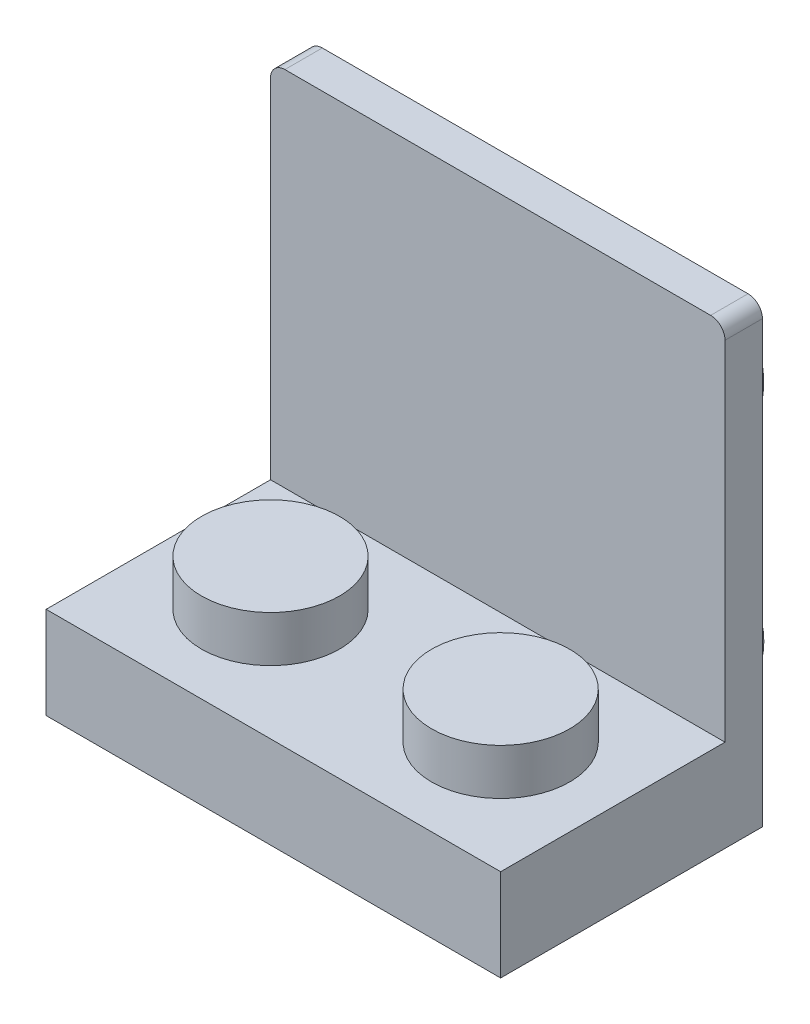
SolidWorks part; units mm, degrees
material "ABS"
ref_plane "Front Plane" through (0, 0, 0) normal (0, 0, 1) x (1, 0, 0)
ref_plane "Top Plane" through (0, 0, 0) normal (0, 1, 0) x (1, 0, 0)
ref_plane "Right Plane" through (0, 0, 0) normal (1, 0, 0) x (0, 0, -1)
sketch "Sketch1" plane through (0, 0, 0) normal (0, 0, 1) x (1, 0, 0)
  line L1 (0, 0) -> (15.8, 0)
  line L2 (0, 0) -> (0, 3.2)
  line L3 (0, 3.2) -> (15.8, 3.2)
  line L4 (15.8, 0) -> (15.8, 3.2)
  line L5 (0, 0) -> (15.8, 3.2) construction
  line L6 (0, 3.2) -> (15.8, 0) construction
  point P4 (7.9, 1.6)
  dimension "D1" = 15.8
  dimension "D2" = 3.2
extrude "Boss-Extrude1" add sketch "Sketch1" against normal blind 7.8
sketch "Sketch2" plane through (0, 3.2, 0) normal (0, 1, 0) x (1, 0, 0)
  line L0 (15.8, 0) -> (0, 0) construction
  circle A0 centre (3.9, 3.9) radius 2.4
  dimension "D1" = 4.8
  dimension "D2" = 3.9
  dimension "D3" = 3.9
extrude "Boss-Extrude2" add sketch "Sketch2" along normal blind 1.6
pattern_linear "LPattern1" count 2 spacing 8 along (0, 0, 1) count 4 spacing 8 along (1, 0, 0) of "Boss-Extrude2"
shell "Shell1" thickness 0.8
sketch "Sketch3" plane through (0, 2.4, 0) normal (0, -1, 0) x (1, 0, 0)
  line L0 (0, 0) -> (15.8, 0) construction
  line L1 (0, -7.8) -> (0, 0) construction
  circle A0 centre (7.9, -3.9) radius 1.5
  circle A1 centre (7.9, -3.9) radius 0.6
  dimension "D1" = 3
  dimension "D2" = 1.2
  dimension "D3" = 3.9
  dimension "D4" = 7.9
extrude "Boss-Extrude3" add sketch "Sketch3" along normal offset from surface (2.2 mm away) 0.2 up to face at (7.9, 0, -3.9)
sketch "Sketch4" plane through (0, 0, -7.8) normal (0, 0, -1) x (-1, 0, 0)
  line L0 (-15.8, 0) -> (-15.8, 7.9)
  line L1 (-15.8, 7.9) -> (0, 7.9)
  line L2 (0, 7.9) -> (0, 0)
  line L3 (0, 0) -> (-15.8, 0)
  dimension "D1" = 7.9
extrude "Boss-Extrude4" add sketch "Sketch4" along normal blind 1.3
sketch "Sketch5" plane through (0, 0, -9.1) normal (0, 0, -1) x (-1, 0, 0)
  line L0 (0, 7.9) -> (-15.8, 7.9) construction
  line L1 (-15.8, 7.9) -> (-15.8, 0) construction
  circle A0 centre (-11.9, 4) radius 2.35
  circle A1 centre (-11.9, 4) radius 1.65
  dimension "D1" = 4.7
  dimension "D4" = 0.7
  dimension "D2" = 3.9
  dimension "D3" = 3.9
extrude "Boss-Extrude5" add sketch "Sketch5" along normal blind 1.6
pattern_linear "LPattern2" count 2 spacing 8 along (-1, 0, 0) of "Boss-Extrude5"
sketch "Sketch7" plane through (0, 0, -7) normal (0, 0, 1) x (1, 0, 0)
  line L0 (12.45, 2.4) -> (12.45, 0)
  line L1 (15, 2.4) -> (0.8, 2.4) construction
  line L2 (0.8, 0) -> (15, 0) construction
  line L3 (12.45, 0) -> (11.35, 0)
  line L4 (11.35, 0) -> (11.35, 2.4)
  line L5 (11.35, 2.4) -> (12.45, 2.4)
  line L6 (15.8, 7.9) -> (15.8, 0) construction
  dimension "D1" = 1.1
  dimension "D2" = 3.35
extrude "Boss-Extrude6" add sketch "Sketch7" along normal blind 0.5
pattern_linear "LPattern3" count 3 spacing 4 along (-1, 0, 0) of "Boss-Extrude6"
ref_plane "Plane1" [suppressed] through (0, 7.9, 0) normal (0, 1, 0) x (1, 0, 0)
sketch "Sketch8" plane through (0, 7.9, 0) normal (0, 1, 0) x (1, 0, 0)
  line L4 (0, 7.8) -> (15.8, 7.8)
  line L5 (15.8, 7.8) -> (15.8, 9.1)
  line L6 (15.8, 9.1) -> (0, 9.1)
  line L7 (0, 9.1) -> (0, 7.8)
  line L8 (0, 7.8) -> (15.8, 7.8)
  line L9 (15.8, 7.8) -> (15.8, 9.1)
  line L10 (15.8, 9.1) -> (0, 9.1)
  line L11 (0, 9.1) -> (0, 7.8)
  dimension "D1" = 0
extrude "Boss-Extrude7" add sketch "Sketch8" along normal blind 7.9
mirror "Mirror1" about plane through (0, 7.9, 0) normal (0, 1, 0) of "LPattern2", "Boss-Extrude5"
fillet "Fillet2" radius 0.5 2 edges at (0, 15.8, -8.45) (15.8, 15.8, -8.45)
